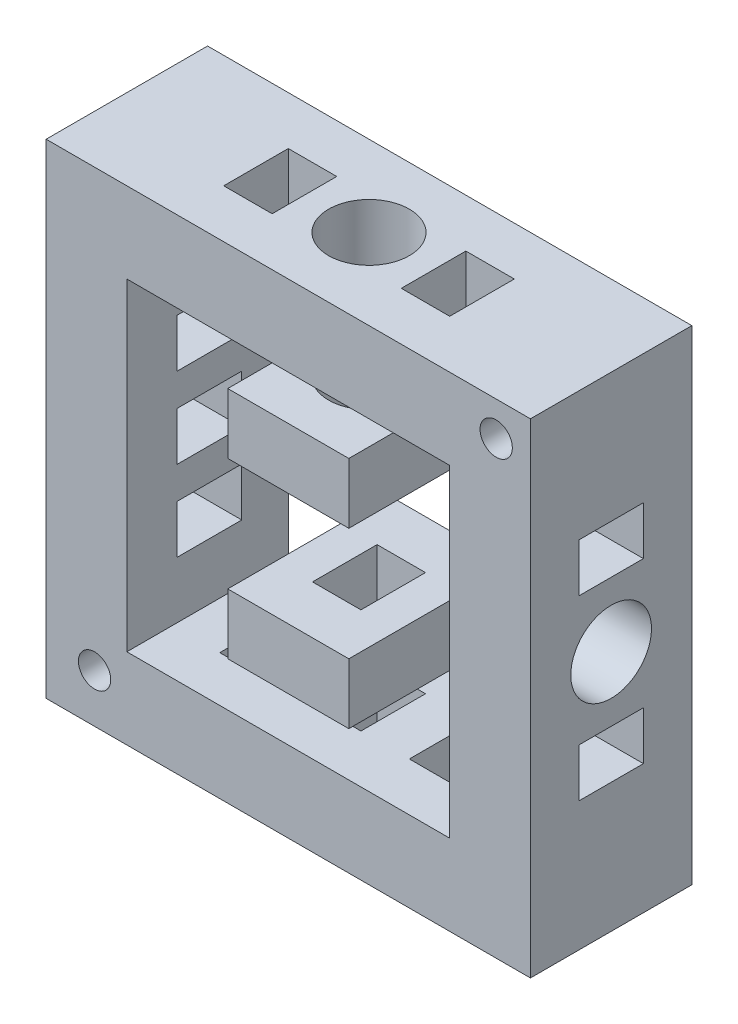
SolidWorks part; units mm, degrees
ref_plane "Front Plane" through (0, 0, 0) normal (0, 0, 1) x (1, 0, 0)
ref_plane "Top Plane" through (0, 0, 0) normal (0, 1, 0) x (1, 0, 0)
ref_plane "Right Plane" through (0, 0, 0) normal (1, 0, 0) x (0, 0, -1)
sketch "Sketch1" plane through (0, 0, 0) normal (0, 0, 1) x (1, 0, 0)
  line L1 (-15, 15) -> (15, 15)
  line L2 (-15, 15) -> (-15, -15)
  line L3 (-15, -15) -> (15, -15)
  line L4 (15, 15) -> (15, -15)
  line L5 (-15, 15) -> (15, -15) construction
  line L6 (-15, -15) -> (15, 15) construction
  point P0 (0, 0)
  dimension "D1" = 30
  dimension "D2" = 30
extrude "Boss-Extrude1" add sketch "Sketch1" along normal blind 10
sketch "Sketch2" plane through (0, 0, 10) normal (0, 0, 1) x (1, 0, 0)
  line L1 (-15, 15) -> (15, 15)
  line L2 (-15, 15) -> (-15, -15)
  line L3 (-15, -15) -> (15, -15)
  line L4 (15, 15) -> (15, -15)
  line L5 (-15, 15) -> (15, -15) construction
  line L6 (-15, -15) -> (15, 15) construction
  line L7 (10, 10) -> (-10, 10)
  line L8 (10, 10) -> (10, -10)
  line L9 (10, -10) -> (-10, -10)
  line L10 (-10, 10) -> (-10, -10)
  line L11 (10, 10) -> (-10, -10) construction
  line L12 (10, -10) -> (-10, 10) construction
  line L13 (0, 0) -> (0, -3.5) construction
  line L14 (0, 0) -> (0, 3.5) construction
  line L15 (-3.75, 7.2488) -> (3.75, 7.2488)
  line L16 (-3.75, 7.2488) -> (-3.75, -7.2488)
  line L17 (-3.75, -7.2488) -> (3.75, -7.2488)
  line L18 (3.75, 7.2488) -> (3.75, -7.2488)
  line L19 (-3.75, 7.2488) -> (3.75, -7.2488) construction
  line L20 (-3.75, -7.2488) -> (3.75, 7.2488) construction
  line L21 (-3.75, 3.5) -> (3.75, 3.5)
  line L22 (-3.75, 3.5) -> (-3.75, -3.5)
  line L23 (-3.75, -3.5) -> (3.75, -3.5)
  line L24 (3.75, 3.5) -> (3.75, -3.5)
  line L25 (-3.75, 3.5) -> (3.75, -3.5) construction
  line L26 (-3.75, -3.5) -> (3.75, 3.5) construction
  point P0 (0, 0)
  point P7 (0, 0)
  line M18 (15, -15) -> (15, 15)
  line M19 (15, 15) -> (-15, 15)
  line M20 (-15, 15) -> (-15, -15)
  line M21 (-15, -15) -> (15, -15)
  dimension "D1" = 20
  dimension "D2" = 20
  dimension "D3" = 3.5
  dimension "D4" = 3.5
  dimension "D5" = 7
  dimension "D6" = 7.5
  dimension "D7" = 7.5
extrude "Boss-Extrude2" add sketch "Sketch2" along normal blind 10 separate body contours L10 L7 L8 L9 M21 M18 M19 M20 | L16 L21 L18 L15 | L23 L16 L17 L18
sketch "Sketch3" plane through (0, 0, 20) normal (0, 0, 1) x (1, 0, 0)
  line L1 (-15, 15) -> (15, 15)
  line L2 (-15, 15) -> (-15, -15)
  line L3 (-15, -15) -> (15, -15)
  line L4 (15, 15) -> (15, -15)
extrude "Boss-Extrude3" add sketch "Sketch3" along normal blind 10 separate body
sketch "Sketch4" plane through (0, 0, 30) normal (0, 0, 1) x (1, 0, 0)
  line L1 (-15, 15) -> (-15, -15) construction
  line L3 (-15, 0) -> (-6, 0) construction
  circle A0 centre (-6, 0) radius 3.1
  dimension "D1" = 9
sketch "Sketch5" plane through (0, 0, 0) normal (0, 0, -1) x (-1, 0, 0)
  line L0 (-15, -0.3729) -> (-6, -0.3729) construction
  line L1 (-15, -15) -> (-15, 15) construction
  circle A0 centre (-6, -0.3729) radius 3.1
  dimension "D1" = 9
extrude "Cut-Extrude1" cut sketch "Sketch4" against normal blind 10
extrude "Cut-Extrude2" cut sketch "Sketch5" against normal blind 10 contours A0
sketch "Sketch8" plane through (0, 0, 30) normal (0, 0, 1) x (1, 0, 0)
  line L0 (-15, -15) -> (-12, -12) construction
  line L1 (-15, -15) -> (15, -15) construction
  line L2 (15, 15) -> (12.8787, 12.8787) construction
  line L3 (15, 15) -> (-15, 15) construction
  circle A0 centre (-12, -12) radius 1
  circle A1 centre (12.8787, 12.8787) radius 1
  dimension "D1" = 3
  dimension "D2" = 45
  dimension "D3" = 3
  dimension "D4" = 45
extrude "Cut-Extrude3" cut sketch "Sketch8" against normal up to surface (30 mm away)
delete or keep bodies "Body-Delete/Keep 1" type delete bodies bodies 111 112
sketch "Sketch9" plane through (0, 15, 0) normal (0, 1, 0) x (1, 0, 0)
  line L0 (15, -15) -> (-15, -15) construction
  line L1 (15, -20) -> (15, -10) construction
  line L2 (-15, -20) -> (-15, -10) construction
  line L3 (0, -15) -> (5.5, -15) construction
  line L4 (0, -15) -> (-5.5, -15) construction
  line L6 (-7, -13) -> (-4, -13)
  line L7 (-7, -13) -> (-7, -17)
  line L8 (-7, -17) -> (-4, -17)
  line L9 (-4, -13) -> (-4, -17)
  line L10 (-7, -13) -> (-4, -17) construction
  line L11 (-7, -17) -> (-4, -13) construction
  line L12 (4, -13) -> (7, -13)
  line L13 (4, -13) -> (4, -17)
  line L14 (4, -17) -> (7, -17)
  line L15 (7, -13) -> (7, -17)
  line L16 (4, -13) -> (7, -17) construction
  line L17 (4, -17) -> (7, -13) construction
  circle A0 centre (0, -15) radius 2.5
  dimension "D1" = 5.5
  dimension "D2" = 5.5
  dimension "D3" = 3
  dimension "D4" = 3
  dimension "D5" = 4
  dimension "D6" = 4
extrude "Cut-Extrude5" cut sketch "Sketch9" against normal up to surface (11.5 mm away)
sketch "Sketch10" plane through (15, 0, 0) normal (1, 0, 0) x (0, 0, -1)
  line L0 (-15, 15) -> (-15, -49985) construction
  line L1 (-20, 15) -> (-10, 15) construction
  line L2 (-20, -15) -> (-10, -15) construction
  line L3 (-15, 0) -> (-15, 5.5) construction
  line L4 (-15, 0) -> (-15, -5.5) construction
  line L6 (-13, 7) -> (-17, 7)
  line L7 (-13, 7) -> (-13, 4)
  line L8 (-13, 4) -> (-17, 4)
  line L9 (-17, 7) -> (-17, 4)
  line L10 (-13, 7) -> (-17, 4) construction
  line L11 (-13, 4) -> (-17, 7) construction
  line L12 (-13, -4) -> (-17, -4)
  line L13 (-13, -4) -> (-13, -7)
  line L14 (-13, -7) -> (-17, -7)
  line L15 (-17, -4) -> (-17, -7)
  line L16 (-13, -4) -> (-17, -7) construction
  line L17 (-13, -7) -> (-17, -4) construction
  circle A0 centre (-15, 0) radius 2.5
  point P4 (-15, 15)
  point P7 (-15, -15)
  dimension "D1" = 5.5
  dimension "D2" = 5.5
  dimension "D3" = 3
  dimension "D4" = 3
  dimension "D5" = 4
  dimension "D6" = 4
extrude "Cut-Extrude6" cut sketch "Sketch10" against normal blind 10
sketch "Sketch11" plane through (-15, 0, 0) normal (-1, 0, 0) x (0, 0, 1)
  line L8 (10, 0) -> (14.8835, 0) construction
  line L9 (10, 15) -> (10, -15) construction
  line L29 (12.8835, 3.5) -> (12.8835, 6.5)
  line L30 (12.8835, -1.5) -> (16.8835, -1.5)
  line L31 (12.8835, -1.5) -> (12.8835, 1.5)
  line L32 (12.8835, 1.5) -> (16.8835, 1.5)
  line L33 (16.8835, -1.5) -> (16.8835, 1.5)
  line L34 (12.8835, -1.5) -> (16.8835, 1.5) construction
  line L35 (12.8835, 1.5) -> (16.8835, -1.5) construction
  line L36 (12.8835, 3.5) -> (16.8835, 3.5)
  line L37 (16.8835, 3.5) -> (16.8835, 6.5)
  line L38 (12.8835, 6.5) -> (16.8835, 6.5)
  line L47 (12.8835, -1.4929) -> (12.8835, 1.5071)
  line L48 (12.8835, -1.4929) -> (16.8835, -1.4929)
  line L49 (16.8835, -1.4929) -> (16.8835, 1.5071)
  line L50 (12.8835, 1.5071) -> (16.8835, 1.5071)
  line L51 (12.8835, 3.5071) -> (12.8835, 6.5071)
  line L52 (12.8835, 3.5071) -> (16.8835, 3.5071)
  line L53 (16.8835, 3.5071) -> (16.8835, 6.5071)
  line L54 (12.8835, 6.5071) -> (16.8835, 6.5071)
  line L59 (12.8835, -6.4858) -> (12.8835, -3.4858)
  line L60 (12.8835, -6.4858) -> (16.8835, -6.4858)
  line L61 (16.8835, -6.4858) -> (16.8835, -3.4858)
  line L62 (12.8835, -3.4858) -> (16.8835, -3.4858)
  line L63 (12.8835, -1.4858) -> (12.8835, 1.5142)
  line L64 (12.8835, -1.4858) -> (16.8835, -1.4858)
  line L65 (16.8835, -1.4858) -> (16.8835, 1.5142)
  line L66 (12.8835, 1.5142) -> (16.8835, 1.5142)
  line L67 (12.8835, 3.5142) -> (12.8835, 6.5142)
  line L68 (12.8835, 3.5142) -> (16.8835, 3.5142)
  line L69 (16.8835, 3.5142) -> (16.8835, 6.5142)
  line L70 (12.8835, 6.5142) -> (16.8835, 6.5142)
  line L71 (12.8835, -6.4929) -> (12.8835, -3.4929)
  line L72 (12.8835, -6.4929) -> (16.8835, -6.4929)
  line L73 (16.8835, -6.4929) -> (16.8835, -3.4929)
  line L74 (12.8835, -3.4929) -> (16.8835, -3.4929)
  line L79 (12.8835, -1.5) -> (12.8835, 3.5) construction
  line L80 (12.8835, 13.5) -> (12.8835, 16.5) [skipped]
  line L81 (12.8835, 16.5) -> (16.8835, 16.5) [skipped]
  line L82 (16.8835, 13.5) -> (16.8835, 16.5) [skipped]
  line L83 (12.8835, 13.5) -> (16.8835, 13.5) [skipped]
  line L84 (12.8835, 8.5) -> (12.8835, 11.5) [skipped]
  line L85 (12.8835, 11.5) -> (16.8835, 11.5) [skipped]
  line L86 (16.8835, 8.5) -> (16.8835, 11.5) [skipped]
  line L87 (12.8835, 8.5) -> (16.8835, 8.5) [skipped]
  line L88 (12.8835, -11.4858) -> (12.8835, -8.4858) [skipped]
  line L89 (12.8835, -8.4858) -> (16.8835, -8.4858) [skipped]
  line L90 (16.8835, -11.4858) -> (16.8835, -8.4858) [skipped]
  line L91 (12.8835, -11.4858) -> (16.8835, -11.4858) [skipped]
  line L92 (12.8835, 8.5071) -> (12.8835, 11.5071) [skipped]
  line L93 (12.8835, 11.5071) -> (16.8835, 11.5071) [skipped]
  line L94 (16.8835, 8.5071) -> (16.8835, 11.5071) [skipped]
  line L95 (12.8835, 8.5071) -> (16.8835, 8.5071) [skipped]
  point P6 (15.9943, 0.4272)
  dimension "D3" = 4
  dimension "D4" = 3
  dimension "D5" = 5
  dimension "D1" = 3
  dimension "D2" = 4
extrude "Cut-Extrude7" cut sketch "Sketch11" against normal blind 9
sketch "Sketch13" plane through (0, -15, 0) normal (0, -1, 0) x (1, 0, 0)
  line L0 (15, 15) -> (-15, 15) construction
  line L1 (15, 20) -> (15, 10) construction
  line L2 (-15, 20) -> (-15, 10) construction
  line L3 (0, 15) -> (0, 10) construction
  line L4 (-15, 10) -> (15, 10) construction
  line L5 (7.5, 13) -> (7.5, 17)
  line L6 (1.5, 13) -> (-1.5, 13)
  line L7 (1.5, 13) -> (1.5, 17)
  line L8 (1.5, 17) -> (-1.5, 17)
  line L9 (-1.5, 13) -> (-1.5, 17)
  line L10 (1.5, 13) -> (-1.5, 17) construction
  line L11 (1.5, 17) -> (-1.5, 13) construction
  line L12 (7.5, 13) -> (4.5, 13)
  line L13 (4.5, 13) -> (4.5, 17)
  line L14 (7.5, 17) -> (4.5, 17)
  line L19 (-4.0767, 13.1667) -> (-4.0767, 17.1667)
  line L20 (-4.0767, 13.1667) -> (-7.0767, 13.1667)
  line L21 (-7.0767, 13.1667) -> (-7.0767, 17.1667)
  line L22 (-4.0767, 17.1667) -> (-7.0767, 17.1667)
  line L43 (1.5, 13) -> (7.5, 13) construction
  line L44 (-21.6533, 13.3334) -> (-21.6533, 17.3334) [skipped]
  line L45 (-21.6533, 17.3334) -> (-24.6533, 17.3334) [skipped]
  line L46 (-24.6533, 13.3334) -> (-24.6533, 17.3334) [skipped]
  line L47 (-21.6533, 13.3334) -> (-24.6533, 13.3334) [skipped]
  line L48 (-15.6533, 13.3334) -> (-15.6533, 17.3334) [skipped]
  line L49 (-15.6533, 17.3334) -> (-18.6533, 17.3334) [skipped]
  line L50 (-18.6533, 13.3334) -> (-18.6533, 17.3334) [skipped]
  line L51 (-15.6533, 13.3334) -> (-18.6533, 13.3334) [skipped]
  line L52 (-9.6533, 13.3334) -> (-9.6533, 17.3334) [skipped]
  line L53 (-9.6533, 17.3334) -> (-12.6533, 17.3334) [skipped]
  line L54 (-12.6533, 13.3334) -> (-12.6533, 17.3334) [skipped]
  line L55 (-9.6533, 13.3334) -> (-12.6533, 13.3334) [skipped]
  line L56 (13.5, 13) -> (13.5, 17) [skipped]
  line L57 (13.5, 17) -> (10.5, 17) [skipped]
  line L58 (10.5, 13) -> (10.5, 17) [skipped]
  line L59 (13.5, 13) -> (10.5, 13) [skipped]
  line L60 (-10.0767, 13.1667) -> (-10.0767, 17.1667) [skipped]
  line L61 (-10.0767, 17.1667) -> (-13.0767, 17.1667) [skipped]
  line L62 (-13.0767, 13.1667) -> (-13.0767, 17.1667) [skipped]
  line L63 (-10.0767, 13.1667) -> (-13.0767, 13.1667) [skipped]
  line L64 (1.9233, 13.1667) -> (1.9233, 17.1667) [skipped]
  line L65 (1.9233, 17.1667) -> (-1.0767, 17.1667) [skipped]
  line L66 (-1.0767, 13.1667) -> (-1.0767, 17.1667) [skipped]
  line L67 (1.9233, 13.1667) -> (-1.0767, 13.1667) [skipped]
  dimension "D1" = 3
  dimension "D2" = 4
  dimension "D5" = 6
  dimension "D3" = 3
  dimension "D4" = 3
extrude "Cut-Extrude9" cut sketch "Sketch13" against normal blind 13 contours L9 L6 L7 L8 | L5 L14 L13 L12 | L19 L22 L21 L20
